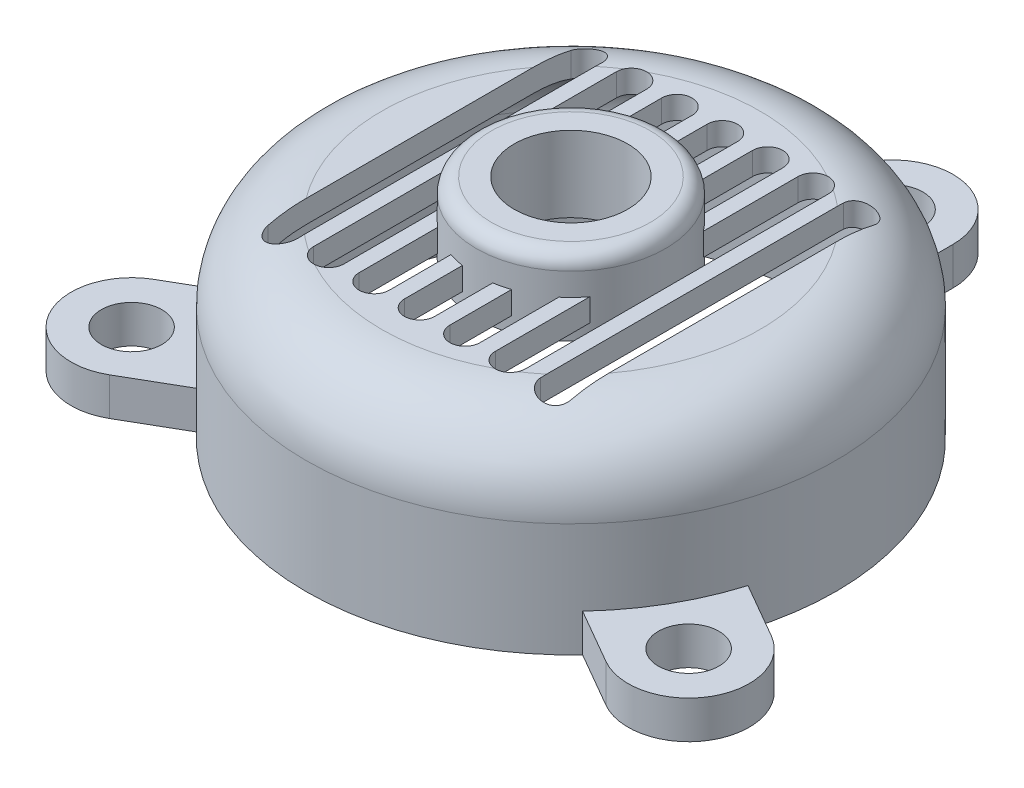
SolidWorks part; units mm, degrees
ref_plane "Front Plane" through (0, 0, 0) normal (0, 0, 1) x (1, 0, 0)
ref_plane "Top Plane" through (0, 0, 0) normal (0, 1, 0) x (1, 0, 0)
ref_plane "Right Plane" through (0, 0, 0) normal (1, 0, 0) x (0, 0, -1)
sketch "Sketch1" plane through (0, 0, 0) normal (0, 1, 0) x (1, 0, 0)
  circle A0 centre (0, 0) radius 35
  dimension "D1" = 70
extrude "Boss-Extrude1" add sketch "Sketch1" along normal blind 25 contours A0
fillet "Fillet1" radius 10 1 edges at (0, 25, 35)
shell "Shell1" thickness 3
ref_plane "Plane1" through (0, 0, 0) normal (0, -1, 0) x (-1, 0, 0)
sketch "Sketch3" plane through (0, 0, 0) normal (0, 1, 0) x (1, 0, 0)
  line L0 (-8, 34.0735) -> (8, 34.0735)
  line L2 (-8, 42.5) -> (-8, 34.0735)
  line L4 (8, 42.5) -> (8, 34.0735)
  circle A0 centre (0, 0) radius 42.5 construction
  circle A1 centre (0, 42.5) radius 4
  arc A2 (8, 42.5) -> (-8, 42.5) centre (0, 42.5) ccw
  circle A3 centre (0, 0) radius 35 construction
extrude "Boss-Extrude2" add sketch "Sketch3" along normal blind 5
pattern_circular "CirPattern1" count 3 over 360 about axis through (0, 0, 0) along (0, 1, 0) of "Boss-Extrude2"
sketch "Sketch4" plane through (0, 25, 0) normal (0, 1, 0) x (1, 0, 0)
  line L0 (-18, 20) -> (-18, -20) construction
  line L1 (-16, 20) -> (-16, -20)
  line L2 (-20, 20) -> (-20, -20)
  arc A0 (-16, 20) -> (-20, 20) centre (-18, 20) ccw
  arc A1 (-20, -20) -> (-16, -20) centre (-18, -20) ccw
  point P2 (-18, 0)
  point P7 (0, 0)
  point P8 (0, 0)
  point P9 (0, 0)
  point P12 (0, 0)
  dimension "D3" = 2
  dimension "D2" = 40
extrude "Cut-Extrude1" cut sketch "Sketch4" against normal through all
sketch "Sketch5" plane through (0, 25, 0) normal (0, 1, 0) x (1, 0, 0)
  line L0 (0, 0) -> (25, 0)
  arc A0 (-16, -19.2094) -> (-16, 19.2094) centre (0, 0) ccw construction
pattern_linear "LPattern1" count 7 spacing 6 along (1, 0, 0) of "Cut-Extrude1"
ref_plane "Plane5" through (0, 25, 0) normal (0, 1, 0) x (1, 0, 0)
sketch "Sketch14" plane through (0, 25, 0) normal (0, 1, 0) x (1, 0, 0)
  circle A0 centre (0, 0) radius 12.5
  dimension "D1" = 25
extrude "Boss-Extrude4" add sketch "Sketch14" along normal blind 5 and the other way blind 5
sketch "Sketch15" plane through (0, 30, 0) normal (0, 1, 0) x (1, 0, 0)
  circle A0 centre (0, 0) radius 7.5
extrude "Cut-Extrude2" cut sketch "Sketch15" against normal through all
fillet "Fillet3" radius 2 1 edges at (0, 30, 12.5)
